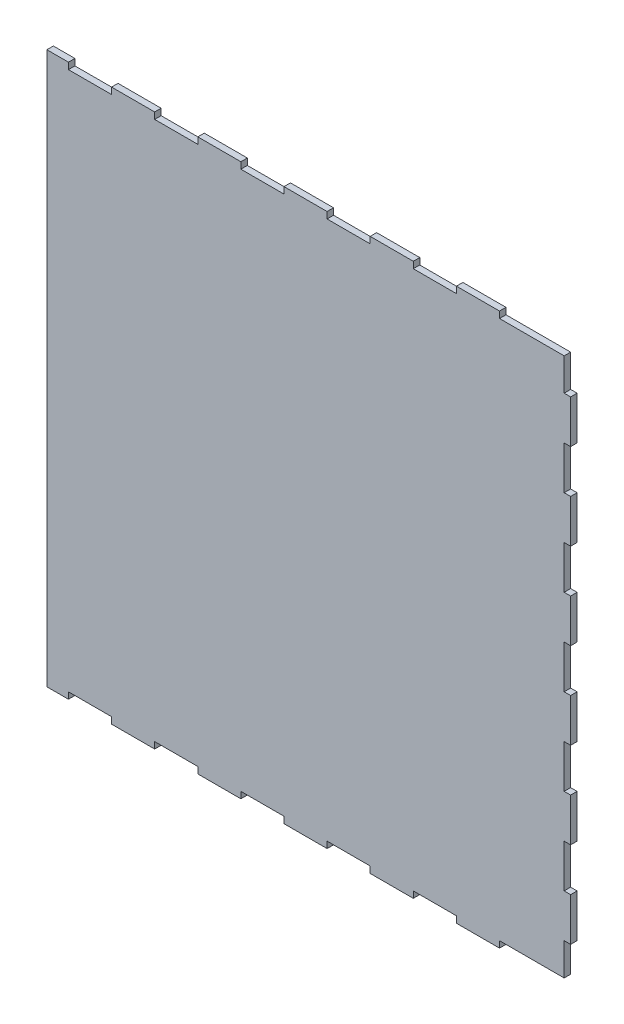
SolidWorks part; units mm, degrees
ref_plane "Front Plane" through (0, 0, 0) normal (0, 0, 1) x (1, 0, 0)
ref_plane "Top Plane" through (0, 0, 0) normal (0, 1, 0) x (1, 0, 0)
ref_plane "Right Plane" through (0, 0, 0) normal (1, 0, 0) x (0, 0, -1)
sketch "Эскиз2" plane through (0, 0, 0) normal (0, 0, 1) x (1, 0, 0)
  line L0 (252.1992, 250.1414) -> (259.9123, 250.1414)
  line L1 (259.9123, 250.1414) -> (259.9123, 254.5354)
  line L2 (259.9123, 254.5354) -> (283.6064, 254.5354)
  line L3 (283.6064, 254.5354) -> (283.6064, 250.1414)
  line L4 (283.6064, 250.1414) -> (305.7717, 250.1414)
  line L5 (305.7717, 250.1414) -> (305.7717, 254.5354)
  line L6 (305.7717, 254.5354) -> (329.4658, 254.5354)
  line L7 (329.4658, 254.5354) -> (329.4658, 250.1414)
  line L8 (329.4658, 250.1414) -> (360.0387, 250.1414)
  line L9 (360.0387, 250.1414) -> (360.0387, 226.7063)
  line L10 (360.0387, 226.7063) -> (365.7711, 226.7063)
  line L11 (365.7711, 226.7063) -> (365.7711, 208.5441)
  line L12 (365.7711, 208.5441) -> (360.0387, 208.5441)
  line L13 (360.0387, 208.5441) -> (360.0387, 191.5536)
  line L14 (360.0387, 191.5536) -> (365.7711, 191.5536)
  line L15 (365.7711, 191.5536) -> (365.7711, 173.3914)
  line L16 (365.7711, 173.3914) -> (360.0387, 173.3914)
  line L17 (360.0387, 173.3914) -> (360.0387, 156.401)
  line L18 (360.0387, 156.401) -> (365.7711, 156.401)
  line L19 (365.7711, 156.401) -> (365.7711, 138.2388)
  line L20 (365.7711, 138.2388) -> (360.0387, 138.2388)
  line L21 (360.0387, 138.2388) -> (360.0387, 121.2484)
  line L22 (360.0387, 121.2484) -> (365.7711, 121.2484)
  line L23 (365.7711, 121.2484) -> (365.7711, 103.0862)
  line L24 (365.7711, 103.0862) -> (360.0387, 103.0862)
  line L25 (360.0387, 103.0862) -> (360.0387, 86.0957)
  line L26 (360.0387, 86.0957) -> (365.7711, 86.0957)
  line L27 (365.7711, 86.0957) -> (365.7711, 67.9335)
  line L28 (365.7711, 67.9335) -> (360.0387, 67.9335)
  line L29 (360.0387, 67.9335) -> (360.0387, 50.9431)
  line L30 (360.0387, 50.9431) -> (365.7711, 50.9431)
  line L31 (365.7711, 50.9431) -> (365.7711, 32.7809)
  line L32 (365.7711, 32.7809) -> (360.0387, 32.7809)
  line L33 (360.0387, 0.0593) -> (328.8776, 0.0593)
  line L34 (328.8776, 0.0593) -> (328.8776, -4.3348)
  line L35 (328.8776, -4.3348) -> (305.1835, -4.3348)
  line L36 (305.1835, -4.3348) -> (305.1835, 0.0593)
  line L37 (305.1835, 0.0593) -> (283.0182, 0.0593)
  line L38 (283.0182, 0.0593) -> (283.0182, -4.3348)
  line L39 (283.0182, -4.3348) -> (259.3241, -4.3348)
  line L40 (259.3241, -4.3348) -> (259.3241, 0.0593)
  line L41 (259.3241, 0.0593) -> (251.611, 0.0593)
  line L42 (251.611, 0.0593) -> (237.1588, 0.0593)
  line L43 (237.1588, 0.0593) -> (237.1588, -4.3348)
  line L44 (237.1588, -4.3348) -> (213.4647, -4.3348)
  line L45 (213.4647, -4.3348) -> (213.4647, 0.0593)
  line L46 (213.4647, 0.0593) -> (191.2994, 0.0593)
  line L47 (191.2994, 0.0593) -> (191.2994, -4.3348)
  line L48 (191.2994, -4.3348) -> (167.6053, -4.3348)
  line L49 (167.6053, -4.3348) -> (167.6053, 0.0593)
  line L50 (167.6053, 0.0593) -> (145.4399, 0.0593)
  line L51 (145.4399, 0.0593) -> (145.4399, -4.3348)
  line L52 (145.4399, -4.3348) -> (121.7459, -4.3348)
  line L53 (121.7459, -4.3348) -> (121.7459, 0.0593)
  line L54 (121.7459, 0.0593) -> (99.5805, 0.0593)
  line L55 (99.5805, 0.0593) -> (99.5805, -4.3348)
  line L56 (99.5805, -4.3348) -> (75.8865, -4.3348)
  line L57 (75.8865, -4.3348) -> (75.8865, 0.0593)
  line L58 (75.8865, 0.0593) -> (53.7211, 0.0593)
  line L59 (53.7211, 0.0593) -> (53.7211, -4.3348)
  line L60 (53.7211, -4.3348) -> (30.0271, -4.3348)
  line L61 (30.0271, -4.3348) -> (30.0271, 0.0593)
  line L62 (30.0271, 0.0593) -> (0.0424, 0.0593)
  line L63 (0.0424, 0.0593) -> (0.0424, 32.7809)
  line L64 (0.0424, 32.7809) -> (-5.6901, 32.7809)
  line L65 (-5.6901, 32.7809) -> (-5.6901, 50.9431)
  line L66 (-5.6901, 50.9431) -> (0.0424, 50.9431)
  line L67 (0.0424, 50.9431) -> (0.0424, 67.9335)
  line L68 (0.0424, 67.9335) -> (-5.6901, 67.9335)
  line L69 (-5.6901, 67.9335) -> (-5.6901, 86.0957)
  line L70 (-5.6901, 86.0957) -> (0.0424, 86.0957)
  line L71 (0.0424, 86.0957) -> (0.0424, 103.0862)
  line L72 (0.0424, 103.0862) -> (-5.6901, 103.0862)
  line L73 (-5.6901, 103.0862) -> (-5.6901, 121.2484)
  line L74 (-5.6901, 121.2484) -> (0.0424, 121.2484)
  line L75 (0.0424, 121.2484) -> (0.0424, 138.2388)
  line L76 (0.0424, 138.2388) -> (-5.6901, 138.2388)
  line L77 (-5.6901, 138.2388) -> (-5.6901, 156.401)
  line L78 (-5.6901, 156.401) -> (0.0424, 156.401)
  line L79 (0.0424, 156.401) -> (0.0424, 173.3914)
  line L80 (0.0424, 173.3914) -> (-5.6901, 173.3914)
  line L81 (-5.6901, 173.3914) -> (-5.6901, 191.5536)
  line L82 (-5.6901, 191.5536) -> (0.0424, 191.5536)
  line L83 (0.0424, 191.5536) -> (0.0424, 208.5441)
  line L84 (0.0424, 208.5441) -> (-5.6901, 208.5441)
  line L85 (-5.6901, 208.5441) -> (-5.6901, 226.7063)
  line L86 (-5.6901, 226.7063) -> (0.0424, 226.7063)
  line L87 (0.0424, 226.7063) -> (0.0424, 250.1414)
  line L88 (0.0424, 250.1414) -> (30.6153, 250.1414)
  line L89 (30.6153, 250.1414) -> (30.6153, 254.5354)
  line L90 (30.6153, 254.5354) -> (54.3093, 254.5354)
  line L91 (54.3093, 254.5354) -> (54.3093, 250.1414)
  line L92 (54.3093, 250.1414) -> (76.4747, 250.1414)
  line L93 (76.4747, 250.1414) -> (76.4747, 254.5354)
  line L94 (76.4747, 254.5354) -> (100.1687, 254.5354)
  line L95 (100.1687, 254.5354) -> (100.1687, 250.1414)
  line L96 (100.1687, 250.1414) -> (122.3341, 250.1414)
  line L97 (122.3341, 250.1414) -> (122.3341, 254.5354)
  line L98 (122.3341, 254.5354) -> (146.0281, 254.5354)
  line L99 (146.0281, 254.5354) -> (146.0281, 250.1414)
  line L100 (146.0281, 250.1414) -> (168.1935, 250.1414)
  line L101 (168.1935, 250.1414) -> (168.1935, 254.5354)
  line L102 (168.1935, 254.5354) -> (191.8876, 254.5354)
  line L103 (191.8876, 254.5354) -> (191.8876, 250.1414)
  line L104 (191.8876, 250.1414) -> (214.0529, 250.1414)
  line L105 (214.0529, 250.1414) -> (214.0529, 254.5354)
  line L106 (214.0529, 254.5354) -> (237.747, 254.5354)
  line L107 (237.747, 254.5354) -> (237.747, 250.1414)
  line L108 (237.747, 250.1414) -> (252.1992, 250.1414)
  line L109 (-2.9475, -11.1911) -> (27.4972, -11.1911)
  line L110 (27.4972, -11.1911) -> (27.4972, -15.5023)
  line L111 (27.4972, -15.5023) -> (51.9003, -15.5023)
  line L112 (51.9003, -15.5023) -> (51.9003, -11.1911)
  line L113 (51.9003, -11.1911) -> (73.3564, -11.1911)
  line L114 (73.3564, -11.1911) -> (73.3564, -15.5023)
  line L115 (73.3564, -15.5023) -> (97.7419, -15.5023)
  line L116 (97.7419, -15.5023) -> (97.7419, -11.1911)
  line L117 (97.7419, -11.1911) -> (119.1409, -11.1911)
  line L118 (119.1409, -11.1911) -> (119.1409, -15.5023)
  line L119 (119.1409, -15.5023) -> (143.6357, -15.5023)
  line L120 (143.6357, -15.5023) -> (143.6357, -11.1911)
  line L121 (143.6357, -11.1911) -> (165.0694, -11.1911)
  line L122 (165.0694, -11.1911) -> (165.0694, -15.5023)
  line L123 (165.0694, -15.5023) -> (189.4359, -15.5023)
  line L124 (189.4359, -15.5023) -> (189.4359, -11.1911)
  line L125 (189.4359, -11.1911) -> (210.8089, -11.1911)
  line L126 (210.8089, -11.1911) -> (210.8089, -15.5023)
  line L127 (210.8089, -15.5023) -> (235.3017, -15.5023)
  line L128 (235.3017, -15.5023) -> (235.3017, -11.1911)
  line L129 (235.3017, -11.1911) -> (256.7496, -11.1911)
  line L130 (256.7496, -11.1911) -> (256.7496, -15.5023)
  line L131 (256.7496, -15.5023) -> (281.117, -15.5023)
  line L132 (281.117, -15.5023) -> (281.117, -11.1911)
  line L133 (281.117, -11.1911) -> (302.5894, -11.1911)
  line L134 (302.5894, -11.1911) -> (302.5894, -15.5023)
  line L135 (302.5894, -15.5023) -> (327.148, -15.5023)
  line L136 (327.148, -15.5023) -> (327.148, -11.1911)
  line L137 (327.148, -11.1911) -> (357.4727, -11.1911)
  line L138 (357.4727, -11.1911) -> (357.4727, -22.8779)
  line L139 (357.4727, -22.8779) -> (365.5155, -22.8779)
  line L140 (365.5155, -22.8779) -> (365.509, -29.7472)
  line L141 (365.509, -29.7472) -> (357.4727, -29.7472)
  line L142 (357.4727, -29.7472) -> (357.4727, -42.673)
  line L143 (357.4727, -42.673) -> (327.148, -42.673)
  line L144 (327.148, -42.673) -> (327.148, -38.9463)
  line L145 (327.148, -38.9463) -> (302.5894, -38.9463)
  line L146 (302.5894, -38.9463) -> (302.5894, -42.673)
  line L147 (302.5894, -42.673) -> (281.117, -42.673)
  line L148 (281.117, -42.673) -> (281.117, -38.9463)
  line L149 (281.117, -38.9463) -> (256.7496, -38.9463)
  line L150 (256.7496, -38.9463) -> (256.7496, -42.673)
  line L151 (256.7496, -42.673) -> (235.3017, -42.673)
  line L152 (235.3017, -42.673) -> (235.3017, -38.9463)
  line L153 (235.3017, -38.9463) -> (210.8089, -38.9463)
  line L154 (210.8089, -38.9463) -> (210.8089, -42.673)
  line L155 (210.8089, -42.673) -> (189.4359, -42.673)
  line L156 (189.4359, -42.673) -> (189.4353, -38.9463)
  line L157 (189.4353, -38.9463) -> (165.0694, -38.9463)
  line L158 (165.0694, -38.9463) -> (165.0694, -42.673)
  line L159 (165.0694, -42.673) -> (143.6357, -42.673)
  line L160 (143.6357, -42.673) -> (143.6357, -38.9463)
  line L161 (143.6357, -38.9463) -> (119.1409, -38.9463)
  line L162 (119.1409, -38.9463) -> (119.1409, -42.673)
  line L163 (119.1409, -42.673) -> (97.7419, -42.673)
  line L164 (97.7419, -42.673) -> (97.7419, -38.9463)
  line L165 (97.7419, -38.9463) -> (73.3564, -38.9463)
  line L166 (73.3564, -38.9463) -> (73.3564, -42.673)
  line L167 (73.3564, -42.673) -> (51.9003, -42.673)
  line L168 (51.9003, -42.673) -> (51.9003, -38.9463)
  line L169 (51.9003, -38.9463) -> (27.4972, -38.9463)
  line L170 (27.4972, -38.9463) -> (27.4972, -42.673)
  line L171 (27.4972, -42.673) -> (-2.9475, -42.673)
  line L172 (-2.9475, -42.673) -> (-2.9475, -29.9471)
  line L173 (-2.9475, -29.9471) -> (-9.6507, -29.9471)
  line L174 (-9.6507, -29.9471) -> (-9.6507, -23.0778)
  line L175 (-9.6507, -23.0778) -> (-2.9475, -23.0778)
  line L176 (-2.9475, -23.0778) -> (-2.9475, -11.1911)
  line L177 (60.6272, -30.2931) -> (60.6272, -23.0367)
  line L178 (60.6272, -23.0367) -> (63.4658, -23.0367)
  line L179 (63.4658, -23.0367) -> (63.4658, -30.2931)
  line L180 (63.4658, -30.2931) -> (60.6272, -30.2931)
  line L181 (30.6174, -30.2532) -> (30.6174, -23.0192)
  line L182 (30.6174, -23.0192) -> (33.456, -23.0192)
  line L183 (33.456, -23.0192) -> (33.456, -30.2532)
  line L184 (33.456, -30.2532) -> (30.6174, -30.2532)
  line L185 (90.633, -30.2432) -> (90.633, -23.0092)
  line L186 (90.633, -23.0092) -> (93.4716, -23.0092)
  line L187 (93.4716, -23.0092) -> (93.4716, -30.2432)
  line L188 (93.4716, -30.2432) -> (90.633, -30.2432)
  line L189 (120.6308, -30.2393) -> (120.6308, -23.0267)
  line L190 (120.6308, -23.0267) -> (123.4694, -23.0267)
  line L191 (123.4694, -23.0267) -> (123.4694, -30.2393)
  line L192 (123.4694, -30.2393) -> (120.6308, -30.2393)
  line L193 (180.6508, -30.1271) -> (180.6508, -23.0192)
  line L194 (180.6508, -23.0192) -> (183.4894, -23.0192)
  line L195 (183.4894, -23.0192) -> (183.4894, -30.1271)
  line L196 (183.4894, -30.1271) -> (180.6508, -30.1271)
  line L197 (153.4727, -23.0191) -> (153.4727, -27.1573)
  line L198 (153.4727, -27.1573) -> (153.4727, -30.1922)
  line L199 (153.4727, -30.1922) -> (150.6341, -30.1922)
  line L200 (150.6341, -30.1922) -> (150.6341, -23.0191)
  line L201 (150.6341, -23.0191) -> (153.4727, -23.0191)
  line L202 (210.6566, -29.9898) -> (210.6566, -23.0192)
  line L203 (210.6566, -23.0192) -> (213.4952, -23.0192)
  line L204 (213.4952, -23.0192) -> (213.4952, -29.9898)
  line L205 (213.4952, -29.9898) -> (210.6566, -29.9898)
  line L206 (244.2529, -30.006) -> (244.2529, -23.0101)
  line L207 (244.2529, -23.0101) -> (247.1018, -23.0101)
  line L208 (247.1018, -23.0101) -> (247.1018, -30.006)
  line L209 (247.1018, -30.006) -> (244.2529, -30.006)
  line L210 (402.371, 242.8158) -> (402.371, 211.9159)
  line L211 (402.371, 211.9159) -> (396.4841, 211.9159)
  line L212 (396.4841, 211.9159) -> (396.4841, 193.3537)
  line L213 (396.4841, 193.3537) -> (402.371, 193.3537)
  line L214 (402.371, 193.3537) -> (402.371, 176.7632)
  line L215 (402.371, 176.7632) -> (396.4841, 176.7632)
  line L216 (396.4841, 176.7632) -> (396.4841, 158.0098)
  line L217 (396.4841, 158.0098) -> (402.371, 158.0098)
  line L218 (402.371, 158.0098) -> (402.371, 141.6106)
  line L219 (402.371, 141.6106) -> (396.4841, 141.6106)
  line L220 (396.4841, 141.6106) -> (396.4841, 123.2484)
  line L221 (396.4841, 123.2484) -> (402.371, 123.2484)
  line L222 (402.371, 123.2484) -> (402.371, 106.458)
  line L223 (402.371, 106.458) -> (396.4841, 106.458)
  line L224 (396.4841, 106.458) -> (396.4841, 87.8958)
  line L225 (396.4841, 87.8958) -> (402.371, 87.8958)
  line L226 (402.371, 87.8958) -> (402.371, 71.3053)
  line L227 (402.371, 71.3053) -> (396.4841, 71.3053)
  line L228 (396.4841, 71.3053) -> (396.4841, 52.9431)
  line L229 (396.4841, 52.9431) -> (402.371, 52.9431)
  line L230 (402.371, 52.9431) -> (402.371, 35.9527)
  line L231 (402.371, 35.9527) -> (396.4841, 35.9527)
  line L232 (396.4841, 35.9527) -> (396.4841, 17.7905)
  line L233 (396.4841, 17.7905) -> (402.371, 17.7905)
  line L234 (402.371, 17.7905) -> (402.371, 8.4645)
  line L235 (402.371, 8.4645) -> (402.371, -22.2271)
  line L236 (402.371, -22.2271) -> (390.3312, -22.2271)
  line L237 (390.3312, -22.2271) -> (390.3312, -14.8105)
  line L238 (390.3312, -14.8105) -> (383.0324, -14.8105)
  line L239 (383.0324, -14.8105) -> (383.0324, -22.2271)
  line L240 (383.0324, -22.2271) -> (370.314, -22.2271)
  line L241 (370.314, 17.7905) -> (376.6791, 17.7905)
  line L242 (376.6791, 17.7905) -> (376.6791, 35.9527)
  line L243 (376.6791, 35.9527) -> (370.314, 35.9527)
  line L244 (370.314, 35.9527) -> (370.314, 52.9431)
  line L245 (370.314, 52.9431) -> (376.6791, 52.9431)
  line L246 (376.6791, 52.9431) -> (376.6791, 71.3053)
  line L247 (376.6791, 71.3053) -> (370.314, 71.3053)
  line L248 (370.314, 71.3053) -> (370.314, 87.8958)
  line L249 (370.314, 87.8958) -> (376.6791, 87.8958)
  line L250 (376.6791, 87.8958) -> (376.6791, 106.458)
  line L251 (376.6791, 106.458) -> (370.314, 106.458)
  line L252 (370.314, 106.458) -> (370.314, 123.2484)
  line L253 (370.314, 123.2484) -> (376.6791, 123.2484)
  line L254 (376.6791, 123.2484) -> (376.6791, 141.6106)
  line L255 (376.6791, 141.6106) -> (370.314, 141.6106)
  line L256 (370.314, 141.6106) -> (370.314, 158.0098)
  line L257 (370.314, 158.0098) -> (376.6791, 158.0098)
  line L258 (376.6791, 158.0098) -> (376.6791, 176.7632)
  line L259 (376.6791, 176.7632) -> (370.314, 176.7632)
  line L260 (370.314, 176.7632) -> (370.314, 193.3537)
  line L261 (370.314, 193.3537) -> (376.6791, 193.3537)
  line L262 (376.6791, 193.3537) -> (376.6791, 211.9159)
  line L263 (376.6791, 211.9159) -> (370.314, 211.9159)
  line L264 (370.314, 211.9159) -> (370.314, 242.8158)
  line L265 (370.314, 242.8158) -> (383.3421, 242.8158)
  line L266 (383.3421, 242.8158) -> (383.3421, 235.2429)
  line L267 (383.3421, 235.2429) -> (390.2615, 235.2429)
  line L268 (390.2615, 235.2429) -> (390.2615, 242.8158)
  line L269 (390.2615, 242.8158) -> (402.371, 242.8158)
  line L270 (382.9975, 171.629) -> (390.2539, 171.629)
  line L271 (390.2539, 171.629) -> (390.2539, 168.7904)
  line L272 (390.2539, 168.7904) -> (382.9975, 168.7904)
  line L273 (382.9975, 168.7904) -> (382.9975, 171.629)
  line L274 (383.0374, 201.6388) -> (390.2714, 201.6388)
  line L275 (390.2714, 201.6388) -> (390.2714, 198.8002)
  line L276 (390.2714, 198.8002) -> (383.0374, 198.8002)
  line L277 (383.0374, 198.8002) -> (383.0374, 201.6388)
  line L278 (383.0474, 141.6232) -> (390.2814, 141.6232)
  line L279 (390.2814, 141.6232) -> (390.2814, 138.7846)
  line L280 (390.2814, 138.7846) -> (383.0474, 138.7846)
  line L281 (383.0474, 138.7846) -> (383.0474, 141.6232)
  line L282 (383.0513, 111.6254) -> (390.2639, 111.6254)
  line L283 (390.2639, 111.6254) -> (390.2639, 108.7868)
  line L284 (390.2639, 108.7868) -> (383.0513, 108.7868)
  line L285 (383.0513, 108.7868) -> (383.0513, 111.6254)
  line L286 (383.1635, 51.6054) -> (390.2714, 51.6054)
  line L287 (390.2714, 51.6054) -> (390.2714, 48.7668)
  line L288 (390.2714, 48.7668) -> (383.1635, 48.7668)
  line L289 (383.1635, 48.7668) -> (383.1635, 51.6054)
  line L290 (390.2715, 78.7835) -> (386.1333, 78.7835)
  line L291 (386.1333, 78.7835) -> (383.0984, 78.7835)
  line L292 (383.0984, 78.7835) -> (383.0984, 81.6221)
  line L293 (383.0984, 81.6221) -> (390.2715, 81.6221)
  line L294 (390.2715, 81.6221) -> (390.2715, 78.7835)
  line L295 (383.3008, 21.5996) -> (390.2714, 21.5996)
  line L296 (390.2714, 21.5996) -> (390.2714, 18.761)
  line L297 (390.2714, 18.761) -> (383.3008, 18.761)
  line L298 (383.3008, 18.761) -> (383.3008, 21.5996)
  spline S0 degree 3 poles (360.0387, 32.7809) (360.0387, 6.279) (360.0387, 29.9698) (360.0387, 0.0593) knots 0.3 0.3 0.3 0.3 0.309091 0.309091 0.309091 0.309091
  spline S1 degree 3 poles (370.314, -22.2271) (370.314, -8.8879) (370.314, 4.4513) (370.314, 17.7905) knots 0.508197 0.508197 0.508197 0.508197 0.52459 0.52459 0.52459 0.52459
sketch "Sketch2" plane through (0, 0, 0) normal (0, 0, 1) x (1, 0, 0)
  line L38 (130.0424, 250.0592) -> (130.0424, 253.0592)
  line L39 (120.0424, 253.0592) -> (130.0424, 253.0592)
  line L40 (150.0424, 250.0592) -> (150.0424, 253.0592)
  line L42 (170.0424, 250.0592) -> (170.0424, 253.0592)
  line L43 (150.0424, 253.0592) -> (170.0424, 253.0592)
  line L44 (190.0424, 250.0592) -> (190.0424, 253.0592)
  line L46 (210.0424, 250.0592) -> (210.0424, 253.0592)
  line L47 (190.0424, 253.0592) -> (210.0424, 253.0592)
  line L48 (230.0424, 250.0592) -> (230.0424, 253.0592)
  line L50 (250.0424, 250.0592) -> (250.0424, 253.0592)
  line L51 (230.0424, 253.0592) -> (250.0424, 253.0592)
  line L52 (270.0424, 250.0592) -> (270.0424, 253.0592)
  line L54 (290.0424, 250.0592) -> (290.0424, 253.0592)
  line L55 (270.0424, 253.0592) -> (290.0424, 253.0592)
  line L56 (310.0424, 250.0592) -> (310.0424, 253.0592)
  line L58 (330.0424, 250.0592) -> (330.0424, 253.0592)
  line L59 (310.0424, 253.0592) -> (330.0424, 253.0592)
  line L60 (360.0424, 125.0592) -> (20.2768, 125.0592) construction
  line L61 (180.0424, 0.0592) -> (180.0424, 110.7569) construction
  line L118 (330.0424, 0.0592) -> (360.0424, 0.0592)
  line L121 (290.0424, 0.0592) -> (310.0424, 0.0592)
  line L122 (170.0424, 250.0592) -> (190.0424, 250.0592)
  line L123 (130.0424, 250.0592) -> (150.0424, 250.0592)
  line L124 (250.0424, 0.0592) -> (270.0424, 0.0592)
  line L126 (210.0424, 250.0592) -> (230.0424, 250.0592)
  line L127 (250.0424, 250.0592) -> (270.0424, 250.0592)
  line L128 (290.0424, 250.0592) -> (310.0424, 250.0592)
  line L129 (330.0424, 250.0592) -> (360.0424, 250.0592)
  line L131 (210.0424, 0.0592) -> (230.0424, 0.0592)
  line L134 (130.0424, 0.0592) -> (150.0424, 0.0592)
  line L136 (170.0424, 0.0592) -> (190.0424, 0.0592)
  line L141 (310.0424, -2.9408) -> (330.0424, -2.9408)
  line L142 (330.0424, 0.0592) -> (330.0424, -2.9408)
  line L143 (310.0424, 0.0592) -> (310.0424, -2.9408)
  line L144 (270.0424, -2.9408) -> (290.0424, -2.9408)
  line L145 (290.0424, 0.0592) -> (290.0424, -2.9408)
  line L146 (270.0424, 0.0592) -> (270.0424, -2.9408)
  line L147 (230.0424, -2.9408) -> (250.0424, -2.9408)
  line L148 (250.0424, 0.0592) -> (250.0424, -2.9408)
  line L149 (230.0424, 0.0592) -> (230.0424, -2.9408)
  line L150 (190.0424, -2.9408) -> (210.0424, -2.9408)
  line L151 (210.0424, 0.0592) -> (210.0424, -2.9408)
  line L152 (190.0424, 0.0592) -> (190.0424, -2.9408)
  line L153 (150.0424, -2.9408) -> (170.0424, -2.9408)
  line L154 (170.0424, 0.0592) -> (170.0424, -2.9408)
  line L155 (150.0424, 0.0592) -> (150.0424, -2.9408)
  line L156 (120.0424, -2.9408) -> (130.0424, -2.9408)
  line L157 (130.0424, 0.0592) -> (130.0424, -2.9408)
  line L165 (360.0424, 250.0592) -> (360.0424, 235.0592)
  line L166 (360.0424, 15.0592) -> (360.0424, 0.0592)
  line L167 (360.0424, 55.0592) -> (360.0424, 35.0592)
  line L168 (360.0424, 95.0592) -> (360.0424, 75.0592)
  line L169 (360.0424, 135.0592) -> (360.0424, 115.0592)
  line L170 (360.0424, 175.0592) -> (360.0424, 155.0592)
  line L171 (360.0424, 215.0592) -> (360.0424, 195.0592)
  line L172 (363.0424, 235.0592) -> (363.0424, 215.0592)
  line L173 (363.0424, 215.0592) -> (360.0424, 215.0592)
  line L174 (363.0424, 235.0592) -> (360.0424, 235.0592)
  line L175 (363.0424, 195.0592) -> (363.0424, 175.0592)
  line L176 (363.0424, 175.0592) -> (360.0424, 175.0592)
  line L177 (363.0424, 195.0592) -> (360.0424, 195.0592)
  line L178 (363.0424, 155.0592) -> (363.0424, 135.0592)
  line L179 (363.0424, 135.0592) -> (360.0424, 135.0592)
  line L180 (363.0424, 155.0592) -> (360.0424, 155.0592)
  line L181 (363.0424, 115.0592) -> (363.0424, 95.0592)
  line L182 (363.0424, 95.0592) -> (360.0424, 95.0592)
  line L183 (363.0424, 115.0592) -> (360.0424, 115.0592)
  line L184 (363.0424, 75.0592) -> (363.0424, 55.0592)
  line L185 (363.0424, 55.0592) -> (360.0424, 55.0592)
  line L186 (363.0424, 15.0592) -> (360.0424, 15.0592)
  line L187 (363.0424, 35.0592) -> (363.0424, 15.0592)
  line L188 (363.0424, 35.0592) -> (360.0424, 35.0592)
  line L189 (363.0424, 75.0592) -> (360.0424, 75.0592)
  line L190 (120.0424, 253.0592) -> (120.0424, -2.9408)
  point P124 (360.0424, 15.0592)
extrude "Boss-Extrude1" add sketch "Sketch2" along normal blind 3
